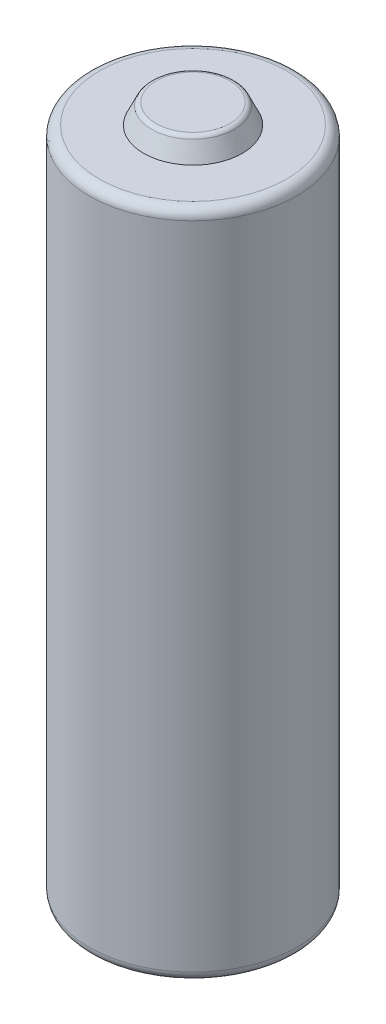
SolidWorks part; units mm, degrees
ref_plane "Front Plane" through (0, 0, 0) normal (0, 0, 1) x (1, 0, 0)
ref_plane "Top Plane" through (0, 0, 0) normal (0, 1, 0) x (1, 0, 0)
ref_plane "Right Plane" through (0, 0, 0) normal (1, 0, 0) x (0, 0, -1)
sketch "Sketch1" plane through (0, 0, 0) normal (0, 1, 0) x (1, 0, 0)
  circle A0 centre (0, 0) radius 10.5
  dimension "D1" = 21
extrude "Boss-Extrude1" add sketch "Sketch1" along normal blind 68
sketch "Sketch2" plane through (0, 68, 0) normal (0, 1, 0) x (1, 0, 0)
  circle A0 centre (0, 0) radius 4.9974
extrude "Boss-Extrude2" add sketch "Sketch2" along normal blind 2 draft 25
sketch "Sketch3" plane through (0, 0, 0) normal (0, -1, 0) x (1, 0, 0)
  circle A0 centre (0, 0) radius 7.0017
  circle A1 centre (0, 0) radius 6.0044
extrude "Cut-Extrude1" cut sketch "Sketch3" against normal blind 3 draft 25
fillet "Fillet1" radius 1 1 edges at (0, 68, 10.5)
fillet "Fillet2" radius 0.5 1 edges at (0, 70, 4.0648)
fillet "Fillet3" radius 1 1 edges at (0, 0, 10.5)
